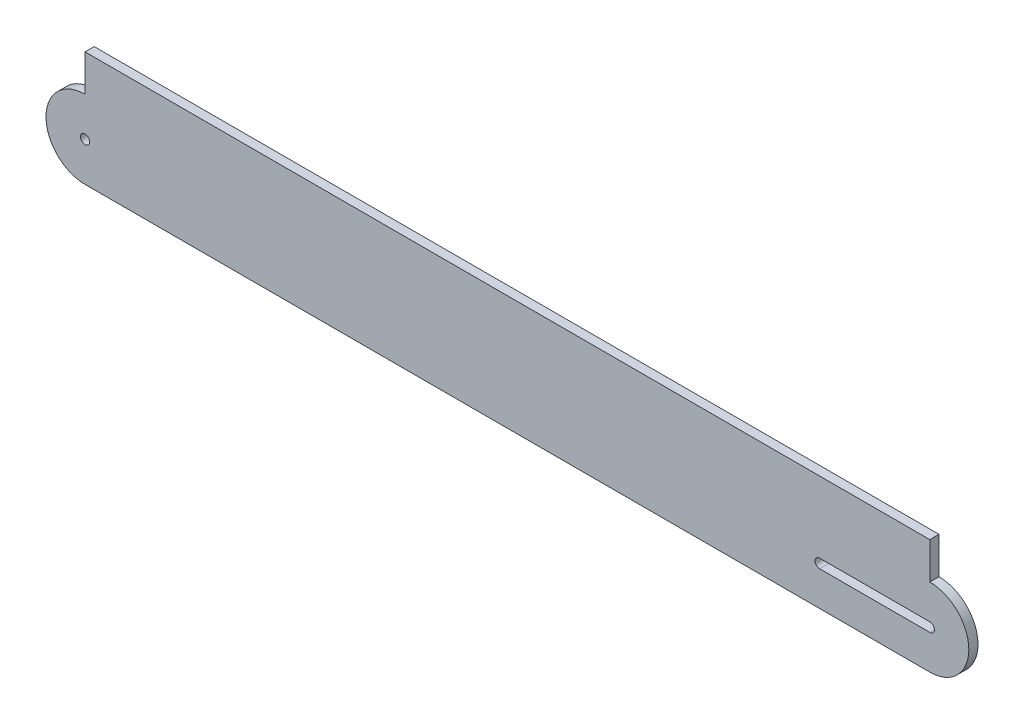
SolidWorks part; units mm, degrees
ref_plane "Front Plane" through (0, 0, 0) normal (0, 0, 1) x (1, 0, 0)
ref_plane "Top Plane" through (0, 0, 0) normal (0, 1, 0) x (1, 0, 0)
ref_plane "Right Plane" through (0, 0, 0) normal (1, 0, 0) x (0, 0, -1)
sketch "Sketch1" plane through (0, 0, 0) normal (0, 0, 1) x (1, 0, 0)
  line L0 (0, 26.9875) -> (584.2, 26.9875)
  line L1 (0, -26.9875) -> (584.2, -26.9875)
  line L2 (0, 26.9875) -> (584.2, 26.9875)
  line L3 (0, 26.9875) -> (0, 52.3875)
  line L4 (584.2, 26.9875) -> (584.2, 52.3875)
  line L5 (0, 52.3875) -> (584.2, 52.3875)
  arc A0 (0, 26.9875) -> (0, -26.9875) centre (0, 0) ccw
  arc A1 (584.2, -26.9875) -> (584.2, 26.9875) centre (584.2, 0) ccw
extrude "Boss-Extrude1" add sketch "Sketch1" along normal mid plane 6.35 contours L5 L3 L0 L4 | L1 A1 L0 A0
sketch "Sketch2" plane through (0, 0, 3.175) normal (0, 0, 1) x (1, 0, 0)
  line L3 (508, 3.175) -> (584.2, 3.175)
  line L4 (508, -3.175) -> (584.2, -3.175)
  arc A1 (584.2, -3.175) -> (584.2, 3.175) centre (584.2, 0) ccw
  arc A3 (508, 3.175) -> (508, -3.175) centre (508, 0) ccw
  circle A5 centre (0, 0) radius 3.175
extrude "Cut-Extrude1" cut sketch "Sketch2" against normal through all
